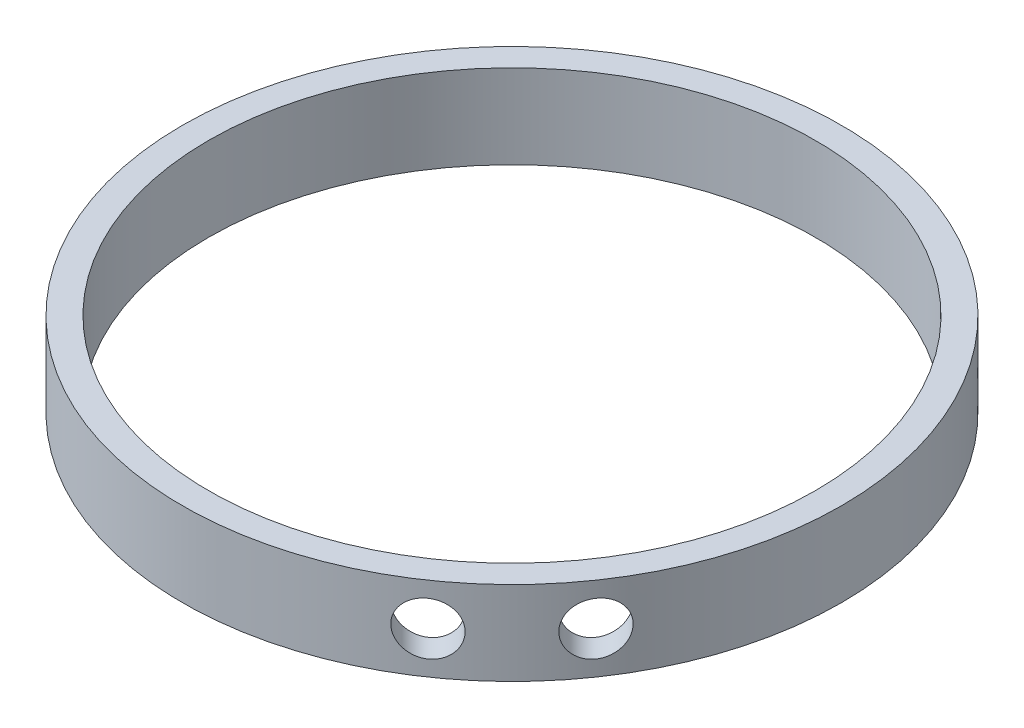
SolidWorks part; units mm, degrees
material "ABS"
ref_plane "Front Plane" through (0, 0, 0) normal (0, 0, 1) x (1, 0, 0)
ref_plane "Top Plane" through (0, 0, 0) normal (0, 1, 0) x (1, 0, 0)
ref_plane "Right Plane" through (0, 0, 0) normal (1, 0, 0) x (0, 0, -1)
sketch "Sketch1" plane through (0, 0, 0) normal (0, 0, 1) x (1, 0, 0)
  line L0 (0, 138.9318) -> (0, -74.0157) construction
  line L1 (44.45, 0) -> (44.45, 204.47)
  line L2 (44.45, 204.47) -> (50.6984, 204.47)
  line L3 (50.6984, 204.47) -> (50.6984, 108.966)
  line L4 (50.6984, 108.966) -> (52.832, 108.966)
  line L5 (52.832, 108.966) -> (52.832, 95.504)
  line L6 (52.832, 95.504) -> (50.6984, 95.504)
  line L7 (50.6984, 95.504) -> (50.6984, 0)
  line L8 (50.6984, 0) -> (44.45, 0)
  dimension "D1" = 88.9
  dimension "D2" = 204.47
  dimension "D3" = 13.462
  dimension "D4" = 101.3968
  dimension "D5" = 105.664
revolve "Revolve1" add sketch "Sketch1" angle 360 about L0
sketch "Sketch2" plane through (0, 204.47, 0) normal (0, 1, 0) x (1, 0, 0)
  circle A0 centre (0, 40.7035) radius 3.7465
  circle A1 centre (0, 0) radius 44.45 construction
  circle A2 centre (0, 40.7035) radius 7.9375
  circle A3 centre (0, 0) radius 50.8 construction
  point P26 (0, 0)
  dimension "D1" = 7.493
  dimension "D2" = 15.875
extrude "Boss-Extrude1" add sketch "Sketch2" against normal up to surface (204.47 mm away) up to face at (-50.6984, 0, 0)
fillet "Fillet1" radius 3.81 2 edges at (-7.2879, 102.235, -43.8485) (7.2879, 102.235, -43.8485)
pattern_circular "CirPattern1" count 4 over 360 about axis through (0, 0, 0) along (0, 1, 0) of "Fillet1", "Boss-Extrude1"
sketch "Sketch3" plane through (0, 204.47, 0) normal (0, 1, 0) x (1, 0, 0)
  circle A1 centre (0, 40.7035) radius 8.636
  dimension "D1" = 17.272
extrude "Cut-Extrude1" cut sketch "Sketch3" against normal blind 12.7
pattern_circular "CirPattern2" count 4 over 360 about axis through (0, 0, 0) along (0, 1, 0) of "Cut-Extrude1"
fillet "Fillet2" radius 2.54 8 edges at (-8.6158, 198.12, -41.2943) (8.6158, 198.12, -41.2943) (41.2943, 198.12, -8.6158) (41.2943, 198.12, 8.6158) (8.6158, 198.12, 41.2943) (-8.6158, 198.12, 41.2943) (-41.2943, 198.12, 8.6158) (-41.2943, 198.12, -8.6158)
ref_plane "Plane1" through (0, 102.235, 0) normal (0, 1, 0) x (1, 0, 0)
mirror "Mirror1" about plane through (0, 102.235, 0) normal (0, 1, 0) of "CirPattern2", "Cut-Extrude1"
fillet "Fillet3" radius 2.54 8 edges at (-41.2943, 6.35, -8.6158) (-41.2943, 6.35, 8.6158) (8.6158, 6.35, 41.2943) (-8.6158, 6.35, 41.2943) (41.2943, 6.35, -8.6158) (41.2943, 6.35, 8.6158) (-8.6158, 6.35, -41.2943) (8.6158, 6.35, -41.2943)
chamfer "Chamfer1" [suppressed] distance 1.27 angle 80
ref_plane "Plane2" through (37.3579, 0, 37.3579) normal (0.7071, 0, 0.7071) x (0, 1, 0)
hole_wizard "5/16 Clearance Hole1" positions "Sketch6" profile "Sketch5" hole size "5/16" standard "ANSI Inch"
sketch "Sketch6" plane through (37.3579, 0, 37.3579) normal (0.7071, 0, 0.7071) x (0, 1, 0)
  line L1 (95.504, 0) -> (108.966, 0)
  line L3 (108.966, -50.6984) -> (108.966, 50.6984) construction
  line L5 (102.235, 9.525) -> (102.235, -9.525)
  line L7 (95.504, 52.832) -> (95.504, -52.832) construction
  point P0 (102.235, -9.525)
  point P2 (102.235, 9.525)
  point P36 (102.235, 0)
  point P40 (102.235, 0)
  dimension "D1" = 19.05
sketch "Sketch5" plane through (44.0931, 102.235, 30.6227) normal (0, 1, 0) x (0.7071, 0, -0.7071)
  line L0 (0, 0) -> (0, 57.3975)
  line L1 (0, 57.3975) -> (4.2164, 54.864)
  line L2 (4.2164, 54.864) -> (4.2164, 0)
  line L5 (4.2164, 0) -> (0, 0)
  line L10 (0, 57.3975) -> (-4.2164, 54.864) construction
  line L11 (0, -6.35) -> (0, 107.95) construction
  dimension "Hole Dia." = 8.4328
  dimension "Hole Depth" = 54.864
  dimension "Drill Angle" = 118
ref_plane "Plane3" through (37.3579, 0, -37.3579) normal (0.7071, 0, -0.7071) x (0, 1, 0)
hole_wizard "#6 Clearance Hole1" positions "Sketch7" profile "Sketch8" hole size "#6" standard "ANSI Inch"
sketch "Sketch7" plane through (37.3579, 0, -37.3579) normal (0.7071, 0, -0.7071) x (0, 1, 0)
  line L2 (95.504, 0) -> (108.966, 0)
  line L4 (108.966, -52.832) -> (108.966, 52.832) construction
  line L5 (95.504, 50.6984) -> (95.504, -50.6984) construction
  point P0 (102.235, 0)
  point P21 (102.235, 0)
sketch "Sketch8" plane through (37.3579, 102.235, -37.3579) normal (0, 1, 0) x (-0.7071, 0, -0.7071)
  line L0 (0, 0) -> (0, 56.0048)
  line L1 (0, 56.0048) -> (1.8986, 54.864)
  line L2 (1.8986, 54.864) -> (1.8986, 0)
  line L5 (1.8986, 0) -> (0, 0)
  line L10 (0, 56.0048) -> (-1.8987, 54.864) construction
  line L11 (0, -6.35) -> (0, 107.95) construction
  dimension "Hole Dia." = 3.7973
  dimension "Hole Depth" = 54.864
  dimension "Drill Angle" = 118
pattern_circular "CirPattern3" [suppressed] count 3 every 90
sketch "Sketch9" plane through (0, 204.47, 0) normal (0, 1, 0) x (1, 0, 0)
  circle A0 centre (0, 0) radius 52.832
extrude "Cut-Extrude2" cut sketch "Sketch9" along normal up to surface (95.504 mm away) from surface
sketch "Sketch10" plane through (0, 0, 0) normal (0, 0, 1) x (1, 0, 0)
  line L0 (0, 204.47) -> (0, 95.504) construction
  line L1 (50.6984, 204.47) -> (-50.6984, 204.47) construction
  line L2 (-52.832, 95.504) -> (52.832, 95.504) construction
  line L4 (52.832, 108.966) -> (48.387, 108.966)
  line L5 (52.832, 108.966) -> (52.832, 95.504)
  line L6 (52.832, 95.504) -> (48.387, 95.504)
  line L7 (48.387, 108.966) -> (48.387, 95.504)
  dimension "D1" = 4.445
revolve "Cut-Revolve1" [suppressed] cut sketch "Sketch10" angle 360 about L0
sketch "Sketch11" plane through (0, 0, 0) normal (0, 0, 1) x (1, 0, 0)
  line L0 (-52.832, 95.504) -> (52.832, 95.504) construction
  line L1 (48.641, 95.504) -> (0, 95.504)
  line L2 (48.641, 95.504) -> (48.641, 108.966)
  line L5 (50.6984, 204.47) -> (-50.6984, 204.47) construction
  line L6 (50.6984, 204.47) -> (0, 204.47)
  line L7 (50.6984, 204.47) -> (50.6984, 108.966)
  line L8 (50.6984, 108.966) -> (48.641, 108.966)
  line L10 (0, 95.504) -> (0, 204.47)
  line L11 (50.6984, 108.966) -> (-50.6984, 108.966) construction
  line L12 (7.9239, 204.47) -> (-7.9239, 204.47) construction
  dimension "D1" = 50.6984
  dimension "D2" = 48.641
revolve "Cut-Revolve2" cut sketch "Sketch11" angle 360 about L10
